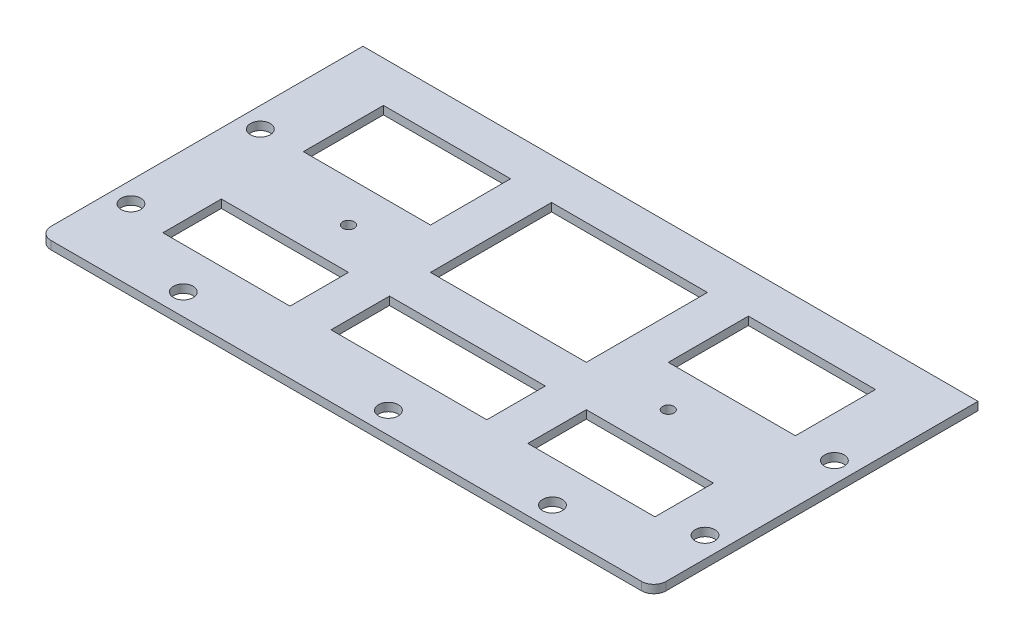
SolidWorks part; units mm, degrees
ref_plane "Plan de face" through (0, 0, 0) normal (0, 0, 1) x (1, 0, 0)
ref_plane "Plan de dessus" through (0, 0, 0) normal (0, 1, 0) x (1, 0, 0)
ref_plane "Plan de droite" through (0, 0, 0) normal (1, 0, 0) x (0, 0, -1)
sketch "Esquisse1" plane through (0, 0, 0) normal (0, 1, 0) x (1, 0, 0)
  line L0 (0, 0) -> (150, 0)
  line L1 (0, 0) -> (0, 79.06)
  line L2 (150, 0) -> (150, 79.06)
  line L3 (0, 79.06) -> (150, 79.06)
  line L4 (0, 39.53) -> (150, 39.53) construction
  line L5 (36, 39.53) -> (75, 79.06) construction
  line L6 (75, 79.06) -> (114, 39.53) construction
  line L7 (15, 69.06) -> (15, 49.53)
  line L8 (15, 69.06) -> (46, 69.06)
  line L9 (15, 49.53) -> (46, 49.53)
  line L10 (46, 69.06) -> (46, 49.53)
  line L11 (56, 69.06) -> (56, 39.53)
  line L12 (56, 69.06) -> (94, 69.06)
  line L13 (56, 39.53) -> (94, 39.53)
  line L14 (94, 69.06) -> (94, 39.53)
  line L15 (104, 69.06) -> (104, 49.53)
  line L16 (104, 69.06) -> (135, 69.06)
  line L17 (104, 49.53) -> (135, 49.53)
  line L18 (135, 69.06) -> (135, 49.53)
  line L19 (135, 29.53) -> (104, 29.53)
  line L20 (135, 29.53) -> (135, 15.27)
  line L21 (104, 29.53) -> (104, 15.27)
  line L22 (135, 15.27) -> (104, 15.27)
  line L23 (94, 29.53) -> (94, 15.27)
  line L24 (94, 29.53) -> (56, 29.53)
  line L25 (94, 15.27) -> (56, 15.27)
  line L26 (56, 29.53) -> (56, 15.27)
  line L27 (46, 29.53) -> (46, 15.27)
  line L28 (46, 29.53) -> (15, 29.53)
  line L29 (46, 15.27) -> (15, 15.27)
  line L30 (15, 29.53) -> (15, 15.27)
  circle A0 centre (5, 49.04) radius 2.4
  circle A1 centre (5, 17.48) radius 2.4
  circle A2 centre (29.99, 5.27) radius 2.4
  circle A3 centre (80, 5.27) radius 2.4
  circle A4 centre (120.01, 5.27) radius 2.4
  circle A5 centre (145, 49.04) radius 2.4
  circle A6 centre (145, 17.48) radius 2.4
  circle A7 centre (36, 39.53) radius 1.4
  circle A8 centre (114, 39.53) radius 1.4
  point P28 (0, 39.53)
  dimension "D3" = 4.8
  dimension "D4" = 4.8
  dimension "D5" = 4.8
  dimension "D6" = 4.8
  dimension "D7" = 4.8
  dimension "D8" = 4.8
  dimension "D9" = 4.8
  dimension "D24" = 2.8
  dimension "D25" = 2.8
  dimension "D1" = 150
  dimension "D2" = 79.06
  dimension "D10" = 5
  dimension "D11" = 5
  dimension "D12" = 5.27
  dimension "D13" = 5.27
  dimension "D14" = 5.27
  dimension "D15" = 5
  dimension "D16" = 5
  dimension "D17" = 17.48
  dimension "D18" = 49.04
  dimension "D19" = 29.99
  dimension "D20" = 70
  dimension "D21" = 29.99
  dimension "D22" = 17.48
  dimension "D23" = 49.04
  dimension "D26" = 78
  dimension "D27" = 10
  dimension "D28" = 10
  dimension "D29" = 10
  dimension "D30" = 10
  dimension "D31" = 10
  dimension "D32" = 10
  dimension "D33" = 10
  dimension "D34" = 10
  dimension "D35" = 10
  dimension "D36" = 20
extrude "Boss.-Extru.1" add sketch "Esquisse1" along normal blind 2
fillet "Congé1" radius 3 2 edges at (150, 1, 0) (0, 1, 0)
